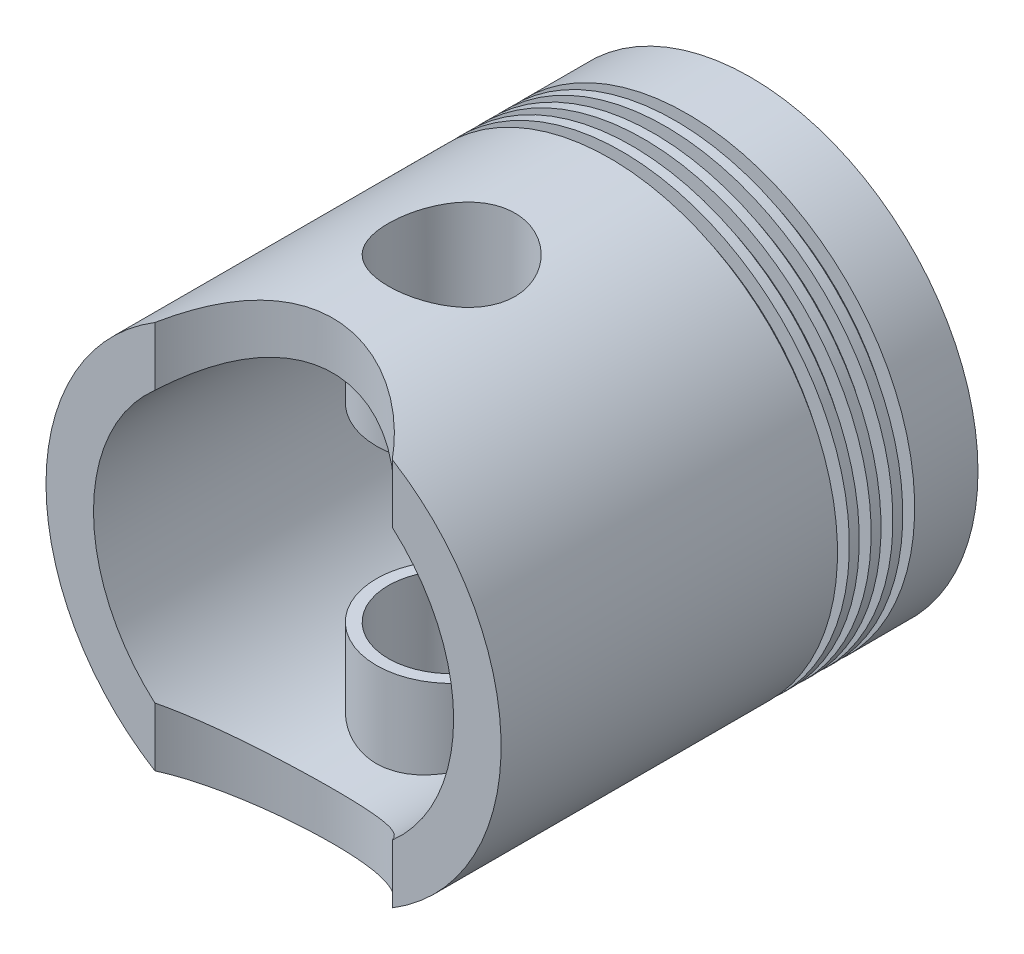
SolidWorks part; units mm, degrees
ref_plane "Front Plane" through (0, 0, 0) normal (0, 0, 1) x (1, 0, 0)
ref_plane "Top Plane" through (0, 0, 0) normal (0, 1, 0) x (1, 0, 0)
ref_plane "Right Plane" through (0, 0, 0) normal (1, 0, 0) x (0, 0, -1)
sketch "Sketch1" plane through (0, 0, 0) normal (0, 1, 0) x (1, 0, 0)
  line L0 (0, 138.646) -> (0, 0) construction
  line L1 (45.5, 0) -> (57.5, 0)
  line L2 (57.5, 0) -> (57.5, 85)
  line L3 (57.5, 85) -> (53.5, 85)
  line L4 (53.5, 85) -> (53.5, 88)
  line L5 (53.5, 88) -> (57.5, 88)
  line L6 (57.5, 88) -> (57.5, 90.5)
  line L7 (57.5, 90.5) -> (53.5, 90.5)
  line L8 (53.5, 90.5) -> (53.5, 93.5)
  line L9 (53.5, 93.5) -> (57.5, 93.5)
  line L10 (57.5, 93.5) -> (57.5, 96)
  line L11 (57.5, 96) -> (53.5, 96)
  line L12 (53.5, 96) -> (53.5, 99)
  line L13 (53.5, 99) -> (57.5, 99)
  line L14 (57.5, 99) -> (57.5, 101.5)
  line L15 (57.5, 101.5) -> (53.5, 101.5)
  line L16 (53.5, 101.5) -> (53.5, 104.5)
  line L17 (53.5, 104.5) -> (57.5, 104.5)
  line L18 (57.5, 104.5) -> (57.5, 120.5)
  line L19 (-22.3826, 131.9585) -> (37.3034, 131.9585) construction
  line L20 (0, 131.9585) -> (0, 116.9585)
  line L22 (45.5, 0) -> (45.5, 109.0598)
  arc A0 (0, 131.9585) -> (57.5, 120.5) centre (0, -18.0415) cw
  arc A1 (0, 116.9585) -> (45.5, 109.0598) centre (0, -18.0415) cw
  arc A2 (0, 116.9585) -> (51.75, 106.6458) centre (0, -18.0415) cw construction
  dimension "D7" = 150
  dimension "D1" = 57.5
  dimension "D2" = 85
  dimension "D3" = 4
  dimension "D4" = 3
  dimension "D5" = 2.5
  dimension "D6" = 16
  dimension "D8" = 15
  dimension "D9" = 45.5
  dimension "D10" = 15
revolve "Revolve1" add sketch "Sketch1" angle 360 about L0
sketch "Sketch2" plane through (0, 0, 0) normal (0, 1, 0) x (1, 0, 0)
  line L0 (0, 131.9585) -> (0, 0) construction
  arc A0 (57.5, 120.5) -> (-57.5, 120.5) centre (0, -18.0415) ccw construction
  circle A1 centre (0, 45) radius 16
  dimension "D1" = 32
  dimension "D2" = 45
extrude "Cut-Extrude1" cut sketch "Sketch2" against normal through all and the other way through all
ref_plane "Plane1" through (0, 24, 0) normal (0, 1, 0) x (1, 0, 0)
sketch "Sketch4" plane through (0, 24, 0) normal (0, 1, 0) x (1, 0, 0)
  circle A0 centre (0, 45) radius 16
  circle A1 centre (0, 45) radius 19
  dimension "D1" = 45
extrude "Boss-Extrude1" add sketch "Sketch4" along normal up to next
mirror "Mirror1" about plane through (0, 0, 0) normal (0, 1, 0) of "Boss-Extrude1"
sketch "Sketch5" plane through (0, 0, 0) normal (0, 1, 0) x (1, 0, 0)
  line L0 (-30, 0) -> (30, 0)
  line L1 (-57.5, 0) -> (57.5, 0) construction
  line L2 (0, 0) -> (0, 15) construction
  arc A0 (-30, 0) -> (30, 0) centre (0, -22.5) cw
  dimension "D1" = 15
  dimension "D2" = 60
extrude "Cut-Extrude2" cut sketch "Sketch5" against normal through all and the other way through all
